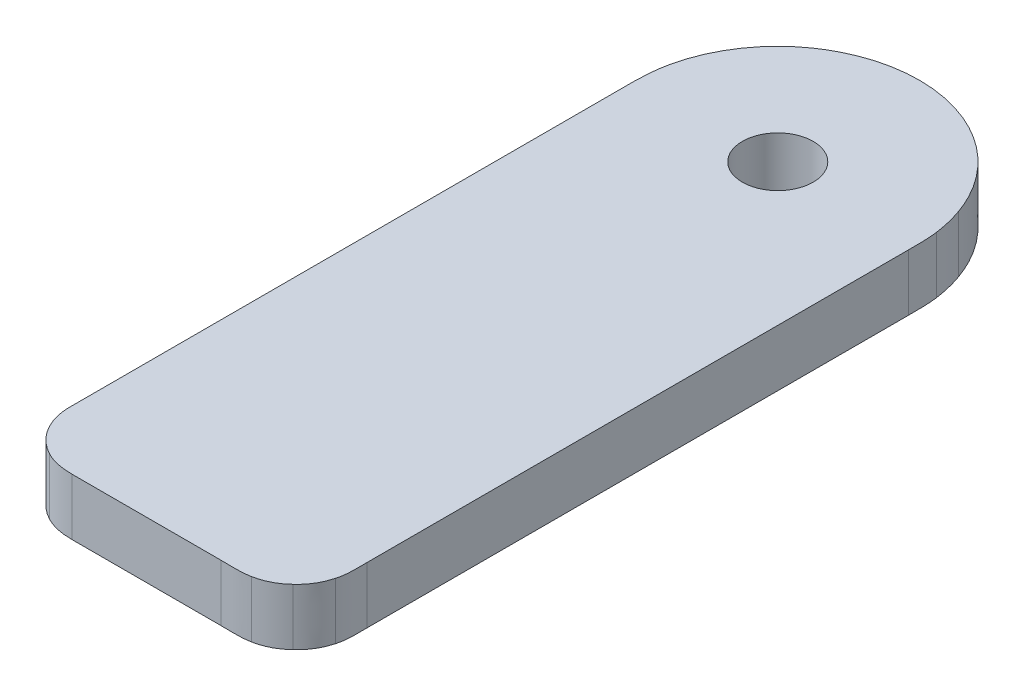
SolidWorks part; units mm, degrees
ref_plane "Front Plane" through (0, 0, 0) normal (0, 0, 1) x (1, 0, 0)
ref_plane "Top Plane" through (0, 0, 0) normal (0, 1, 0) x (1, 0, 0)
ref_plane "Right Plane" through (0, 0, 0) normal (1, 0, 0) x (0, 0, -1)
sketch "Imported Profile" plane through (0, 0, 0) normal (0, 1, 0) x (1, 0, 0)
  spline S0 degree 3 poles (20.0657, 70.137) (20.0657, 72.3281) (18.2881, 74.1058) (16.097, 74.1058) knots 0 0 0 0 1 1 1 1
  spline S1 degree 3 poles (16.097, 74.1058) (13.9059, 74.1058) (12.1282, 72.3281) (12.1282, 70.137) knots 0 0 0 0 1 1 1 1
  spline S2 degree 3 poles (12.1282, 70.137) (12.1282, 67.946) (13.9059, 66.1683) (16.097, 66.1683) knots 0 0 0 0 1 1 1 1
  spline S3 degree 3 poles (16.097, 66.1683) (18.2881, 66.1683) (20.0657, 67.946) (20.0657, 70.137) knots 0 0 0 0 1 1 1 1
  spline S4 degree 3 poles (0.2289, 6.5888) (0.2289, 24.586) (0.2289, 42.5832) (0.2289, 60.5803) knots 0 0 0 0 1 1 1 1
  spline S5 degree 3 poles (0.2289, 60.5803) (0.2289, 62.7714) (0.2289, 64.9694) (0.2289, 67.1605) knots 0 0 0 0 1 1 1 1
  spline S6 degree 3 poles (0.2289, 67.1605) (0.2289, 69.3102) (0.1324, 71.4324) (0.6078, 73.5821) knots 0 0 0 0 1 1 1 1
  spline S7 degree 3 poles (0.6078, 73.5821) (1.6414, 78.1986) (4.68, 82.1122) (8.8968, 84.255) knots 0 0 0 0 1 1 1 1
  spline S8 degree 3 poles (8.8968, 84.255) (17.4475, 88.6096) (27.8241, 84.4895) (31.0487, 75.4563) knots 0 0 0 0 1 1 1 1
  spline S9 degree 3 poles (31.0487, 75.4563) (31.4346, 74.3814) (31.6964, 73.2927) (31.848, 72.1627) knots 0 0 0 0 1 1 1 1
  spline S10 degree 3 poles (31.848, 72.1627) (31.9857, 71.0741) (31.9789, 69.9854) (31.9789, 68.8968) knots 0 0 0 0 1 1 1 1
  spline S11 degree 3 poles (31.9789, 68.8968) (31.9789, 66.6368) (31.9789, 64.3768) (31.9789, 62.1237) knots 0 0 0 0 1 1 1 1
  spline S12 degree 3 poles (31.9789, 62.1237) (31.9789, 57.6038) (31.9789, 53.0907) (31.9789, 48.5776) knots 0 0 0 0 1 1 1 1
  spline S13 degree 3 poles (31.9789, 48.5776) (31.9789, 39.5652) (31.9789, 30.5598) (31.9789, 21.5543) knots 0 0 0 0 1 1 1 1
  spline S14 degree 3 poles (31.9789, 21.5543) (31.9789, 17.0963) (31.9789, 12.6384) (31.9789, 8.1873) knots 0 0 0 0 1 1 1 1
  spline S15 degree 3 poles (31.9789, 8.1873) (31.9789, 7.0918) (32.0547, 6.01) (31.7515, 4.9145) knots 0 0 0 0 1 1 1 1
  spline S16 degree 3 poles (31.7515, 4.9145) (31.4207, 3.7087) (30.8558, 2.7785) (29.9394, 1.931) knots 0 0 0 0 1 1 1 1
  spline S17 degree 3 poles (29.9394, 1.931) (29.0299, 1.0835) (28.0721, 0.6012) (26.8526, 0.3601) knots 0 0 0 0 1 1 1 1
  spline S18 degree 3 poles (26.8526, 0.3601) (25.757, 0.1466) (24.6684, 0.2431) (23.5728, 0.2431) knots 0 0 0 0 1 1 1 1
  spline S19 degree 3 poles (23.5728, 0.2431) (19.1218, 0.2431) (14.6707, 0.2431) (10.2196, 0.2431) knots 0 0 0 0 1 1 1 1
  spline S20 degree 3 poles (10.2196, 0.2431) (9.1034, 0.2431) (7.9872, 0.2431) (6.8779, 0.2431) knots 0 0 0 0 1 1 1 1
  spline S21 degree 3 poles (6.8779, 0.2431) (5.7272, 0.2431) (4.7006, 0.4156) (3.6533, 0.9528) knots 0 0 0 0 1 1 1 1
  spline S22 degree 3 poles (3.6533, 0.9528) (1.5449, 2.0414) (0.2289, 4.2118) (0.2289, 6.589) knots 0 0 0 0 1 1 1 1
sketch "Sketch2" plane through (0, 0, 0) normal (0, 1, 0) x (1, 0, 0)
  line L0 (0.2289, 6.6145) -> (0.2289, 6.612)
  circle A0 centre (16.097, 70.137) radius 3.9688
  spline S0 degree 3 poles (1446.7015, -1290.5903) (-1780.0274, 1069.7301) (2009.0623, -433.3076) (-1958.1866, 60.3871) knots -5.403545 -5.403545 -5.403545 -5.403545 6.402107 6.402107 6.402107 6.402107 only from (8.8968, 84.255) to (31.0487, 75.4563) construction
  spline S1 degree 3 poles (0.2289, -1993.3987) (0.2289, -643.8023) (0.2289, 711.109) (0.2289, 2060.5617) knots -37.066534 -37.066534 -37.066534 -37.066534 38.068418 38.068418 38.068418 38.068418 only from (0.2289, 6.5888) to (0.2289, 60.5803) construction
  spline S2 degree 3 poles (0.2289, 2060.5773) (0.2289, -2420.9426) (0.2289, 2548.6847) (0.2289, -1932.7977) knots -55.106369 -55.106369 -55.106369 -55.106369 56.107997 56.107997 56.107997 56.107997 only from (0.2289, 60.5803) to (0.2289, 67.1605) construction
  spline S3 degree 3 poles (-1981.0959, -199.6544) (1983.764, 204.7629) (-1984.7338, -60.5547) (1985.8024, 312.0134) knots -14.221917 -14.221917 -14.221917 -14.221917 14.520918 14.520918 14.520918 14.520918 only from (0.2289, 67.1605) to (0.6078, 73.5821) construction
  spline S4 degree 3 poles (1736.2437, 1042.8188) (-1446.1997, -1367.6461) (1041.9934, 1845.7766) (-495.3253, -1838.6594) knots -10.86182 -10.86182 -10.86182 -10.86182 11.856834 11.856834 11.856834 11.856834 only from (0.6078, 73.5821) to (8.8968, 84.255) construction
  spline S5 degree 3 poles (-1264.4463, 1596.4281) (993.3443, -1421.6174) (-608.9342, 1710.8461) (366.7885, -1894.1782) knots -37.517411 -37.517411 -37.517411 -37.517411 40.055017 40.055017 40.055017 40.055017 only from (31.0487, 75.4563) to (31.848, 72.1627) construction
  spline S6 degree 3 poles (-1966.2969, 146.5495) (2030.1603, 94.4332) (-1966.0788, 43.6595) (2029.8835, -8.4516) knots -22.673416 -22.673416 -22.673416 -22.673416 24.58141 24.58141 24.58141 24.58141 only from (31.848, 72.1627) to (31.9789, 68.8968) construction
  spline S7 degree 3 poles (31.9789, -1931.0157) (31.9789, 2706.5516) (31.9789, -2566.0904) (31.9789, 2062.0427) knots -70.798339 -70.798339 -70.798339 -70.798339 70.752749 70.752749 70.752749 70.752749 only from (31.9789, 68.8968) to (31.9789, 62.1237) construction
  spline S8 degree 3 poles (31.9789, 2062.1026) (31.9789, -935.7668) (31.9789, 1031.3833) (31.9789, -1951.3868) knots -55.76006 -55.76006 -55.76006 -55.76006 57.594898 57.594898 57.594898 57.594898 only from (31.9789, 62.1237) to (31.9789, 48.5776) construction
  spline S9 degree 3 poles (31.9789, 2048.5473) (31.9789, -284.9875) (31.9789, 332.4805) (31.9789, -1978.4154) knots -46.509883 -46.509883 -46.509883 -46.509883 48.138107 48.138107 48.138107 48.138107 only from (31.9789, 48.5776) to (31.9789, 21.5543) construction
  spline S10 degree 3 poles (31.9789, -1978.3867) (31.9789, 3369.4761) (31.9789, -3319.6415) (31.9789, 2008.0996) knots -75.845022 -75.845022 -75.845022 -75.845022 75.718235 75.718235 75.718235 75.718235 only from (31.9789, 21.5543) to (31.9789, 8.1873) construction
  spline S11 degree 3 poles (2023.4607, 189.6272) (-1960.9035, -98.0158) (2025.4517, 108.3845) (-1961.2397, -159.6725) knots -16.193378 -16.193378 -16.193378 -16.193378 16.531581 16.531581 16.531581 16.531581 only from (31.9789, 8.1873) to (31.7515, 4.9145) construction
  spline S12 degree 3 poles (683.6197, 1892.957) (-814.5196, -1660.3893) (1118.0776, 1520.1917) (-1345.8354, -1446.1591) knots -19.781941 -19.781941 -19.781941 -19.781941 20.790634 20.790634 20.790634 20.790634 only from (31.7515, 4.9145) to (29.9394, 1.931) construction
  spline S13 degree 3 poles (1528.2872, 1323.403) (-1522.0116, -1055.3293) (1710.4379, 827.8021) (-1867.1363, -634.2808) knots -19.148923 -19.148923 -19.148923 -19.148923 20.284956 20.284956 20.284956 20.284956 only from (29.9394, 1.931) to (26.8526, 0.3601) construction
  spline S14 degree 3 poles (145.2225, 1996.62) (-24.2784, -1997.4787) (75.0827, 1997.7082) (-102.793, -1995.4517) knots -16.238552 -16.238552 -16.238552 -16.238552 17.761798 17.761798 17.761798 17.761798 only from (26.8526, 0.3601) to (23.5728, 0.2431) construction
  spline S15 degree 3 poles (2023.571, 0.2431) (820.1959, 0.2431) (-783.4394, 0.2431) (-1989.7641, 0.2431) knots -157.325799 -157.325799 -157.325799 -157.325799 158.159052 158.159052 158.159052 158.159052 only from (23.5728, 0.2431) to (10.2196, 0.2431) construction
  spline S16 degree 3 poles (-1989.7187, 0.2431) (2316.0901, 0.2431) (-2294.3927, 0.2431) (2006.8548, 0.2431) knots -68.767462 -68.767462 -68.767462 -68.767462 68.732283 68.732283 68.732283 68.732283 only from (10.2196, 0.2431) to (6.8779, 0.2431) construction
  spline S17 degree 3 poles (1439.0775, -1392.29) (-1199.8691, 1502.0312) (1088.8798, -1605.1989) (-1044.6347, 1703.9339) knots -20.29254 -20.29254 -20.29254 -20.29254 19.837415 19.837415 19.837415 19.837415 only from (6.8779, 0.2431) to (3.6533, 0.9528) construction
  spline S18 degree 3 poles (-480.8763, 1935.0374) (872.3055, -1828.3282) (-1201.197, 1636.7618) (1476.4461, -1333.5227) knots -11.986955 -11.986955 -11.986955 -11.986955 13.008823 13.008823 13.008823 13.008823 only from (3.6533, 0.9528) to (0.2289, 6.589) construction
  spline S19 degree 3 poles (8.8968, 84.255) (17.4475, 88.6096) (27.8241, 84.4895) (31.0487, 75.4563) knots 0 0 0 0 1 1 1 1
  spline S20 degree 3 poles (0.2289, 6.612) (0.2289, 24.6015) (0.2289, 42.5909) (0.2289, 60.5803) knots 0.000431 0.000431 0.000431 0.000431 1 1 1 1
  spline S21 degree 3 poles (0.2289, 60.5803) (0.2289, 62.7714) (0.2289, 64.9694) (0.2289, 67.1605) knots 0 0 0 0 1 1 1 1
  spline S22 degree 3 poles (0.2289, 67.1605) (0.2289, 69.3102) (0.1324, 71.4324) (0.6078, 73.5821) knots 0 0 0 0 1 1 1 1
  spline S23 degree 3 poles (0.6078, 73.5821) (1.6414, 78.1986) (4.68, 82.1122) (8.8968, 84.255) knots 0 0 0 0 1 1 1 1
  spline S24 degree 3 poles (31.0487, 75.4563) (31.4346, 74.3814) (31.6964, 73.2927) (31.848, 72.1627) knots 0 0 0 0 1 1 1 1
  spline S25 degree 3 poles (31.848, 72.1627) (31.9857, 71.0741) (31.9789, 69.9854) (31.9789, 68.8968) knots 0 0 0 0 1 1 1 1
  spline S26 degree 3 poles (31.9789, 68.8968) (31.9789, 66.6368) (31.9789, 64.3768) (31.9789, 62.1237) knots 0 0 0 0 1 1 1 1
  spline S27 degree 3 poles (31.9789, 62.1237) (31.9789, 57.6038) (31.9789, 53.0907) (31.9789, 48.5776) knots 0 0 0 0 1 1 1 1
  spline S28 degree 3 poles (31.9789, 48.5776) (31.9789, 39.5652) (31.9789, 30.5598) (31.9789, 21.5543) knots 0 0 0 0 1 1 1 1
  spline S29 degree 3 poles (31.9789, 21.5543) (31.9789, 17.0963) (31.9789, 12.6384) (31.9789, 8.1873) knots 0 0 0 0 1 1 1 1
  spline S30 degree 3 poles (31.9789, 8.1873) (31.9789, 7.0918) (32.0547, 6.01) (31.7515, 4.9145) knots 0 0 0 0 1 1 1 1
  spline S31 degree 3 poles (31.7515, 4.9145) (31.4207, 3.7087) (30.8558, 2.7785) (29.9394, 1.931) knots 0 0 0 0 1 1 1 1
  spline S32 degree 3 poles (29.9394, 1.931) (29.0299, 1.0835) (28.0721, 0.6012) (26.8526, 0.3601) knots 0 0 0 0 1 1 1 1
  spline S33 degree 3 poles (26.8526, 0.3601) (25.757, 0.1466) (24.6684, 0.2431) (23.5728, 0.2431) knots 0 0 0 0 1 1 1 1
  spline S34 degree 3 poles (23.5728, 0.2431) (19.1218, 0.2431) (14.6707, 0.2431) (10.2196, 0.2431) knots 0 0 0 0 1 1 1 1
  spline S35 degree 3 poles (10.2196, 0.2431) (9.1034, 0.2431) (7.9872, 0.2431) (6.8779, 0.2431) knots 0 0 0 0 1 1 1 1
  spline S36 degree 3 poles (6.8779, 0.2431) (5.7272, 0.2431) (4.7006, 0.4156) (3.6533, 0.9528) knots 0 0 0 0 1 1 1 1
  spline S37 degree 3 poles (3.6533, 0.9528) (1.5373, 2.0453) (0.2194, 4.2274) (0.2289, 6.6145) knots 0 0 0 0 1.003586 1.003586 1.003586 1.003586
  dimension "D1" = 0.0025
extrude "Boss-Extrude1" add sketch "Sketch2" along normal blind 6.35 contours S37 S36 S35 S34 S33 S32 S31 S30 S29 S28 S27 S26 S25 S24 S19 S23 S22 S21 S20 L0 A0
ref_plane "Plane1" through (16.1039, 0, 0) normal (1, 0, 0) x (0, 0, -1)
